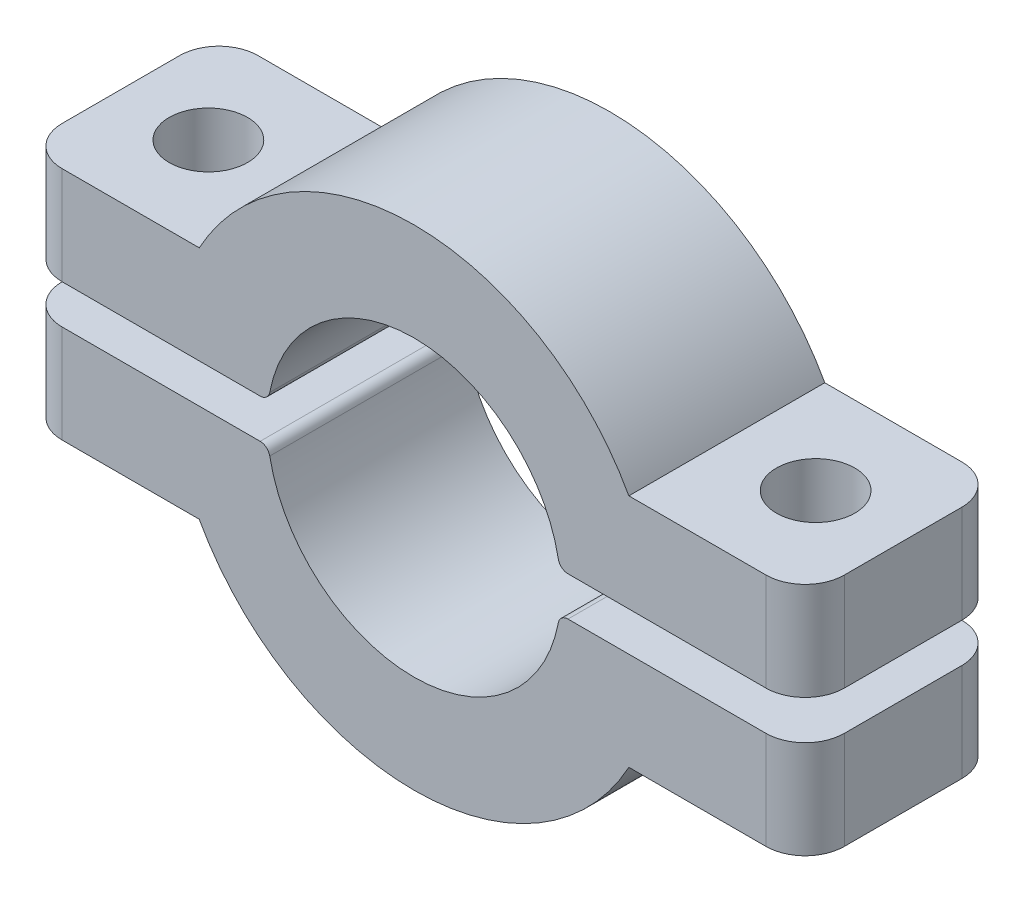
SolidWorks part; units mm, degrees
ref_plane "Front Plane" through (0, 0, 0) normal (0, 0, 1) x (1, 0, 0)
ref_plane "Top Plane" through (0, 0, 0) normal (0, 1, 0) x (1, 0, 0)
ref_plane "Right Plane" through (0, 0, 0) normal (1, 0, 0) x (0, 0, -1)
sketch "Sketch1" plane through (0, 0, 0) normal (0, 0, 1) x (1, 0, 0)
  line L0 (-19.9659, 1) -> (-7.433, 1)
  line L1 (7.433, 1) -> (19.9659, 1)
  line L2 (19.9659, 1) -> (19.9659, 6)
  line L3 (19.9659, 6) -> (10.9659, 6)
  line L4 (-10.9659, 6) -> (-19.9659, 6)
  line L5 (-19.9659, 6) -> (-19.9659, 1)
  line L6 (0, -5.5) -> (0, 5.5) construction
  arc A0 (-7.433, 1) -> (7.433, 1) centre (0, 0) cw
  arc A2 (-10.9659, 6) -> (10.9659, 6) centre (0, 0) cw
  dimension "D2" = 7.5
  dimension "D1" = 5
  dimension "D3" = 5
  dimension "D4" = 9
  dimension "D5" = 9
  dimension "D6" = 1
extrude "Boss-Extrude1" add sketch "Sketch1" along normal blind 10
fillet "Fillet1" radius 2 4 edges at (19.9659, 3.5, 0) (-19.9659, 3.5, 0) (19.9659, 3.5, 10) (-19.9659, 3.5, 10)
fillet "Fillet3" radius 0.5 2 edges at (-7.433, 1, 5) (7.433, 1, 5)
mirror "Mirror3" about plane through (0, 0, 0) normal (0, 1, 0) of bodies 101
sketch "Sketch3" plane through (0, 0, 0) normal (0, 1, 0) x (1, 0, 0)
  line L0 (-13.75, 0) -> (13.75, 0) construction
  line L1 (0, -5.5) -> (0, 5.5) construction
  circle A0 centre (-15.5, -5) radius 2
  circle A1 centre (15.5, -5) radius 2
  dimension "D3" = 5
  dimension "D2" = 4
  dimension "D4" = 5
  dimension "D5" = 15.5
  dimension "D6" = 15.5
extrude "Cut-Extrude1" cut sketch "Sketch3" against normal through all both and the other way through all
equation "\"shaftDiameter\"= 14mm"
equation "\"D2@Sketch1\"=\"shaftDiameter\"/2 +0.5"
equation "\"D5@Sketch3\"=\"shaftDiameter\"/2+8.5"
equation "\"D6@Sketch3\"=\"D5@Sketch3\""
equation "\"holeDiameter\"= 4mm"
equation "\"D2@Sketch3\"=\"holeDiameter\""
